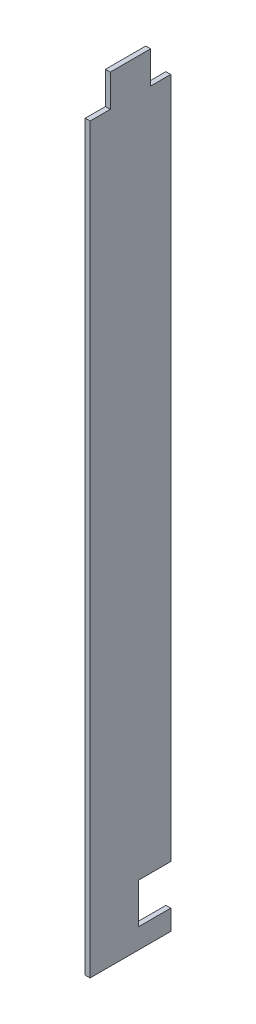
SolidWorks part; units mm, degrees
ref_plane "Plan de face" through (0, 0, 0) normal (0, 0, 1) x (1, 0, 0)
ref_plane "Plan de dessus" through (0, 0, 0) normal (0, 1, 0) x (1, 0, 0)
ref_plane "Plan de droite" through (0, 0, 0) normal (1, 0, 0) x (0, 0, -1)
sketch "Esquisse1" plane through (0, 0, 0) normal (1, 0, 0) x (0, 0, -1)
  line L1 (25, -230) -> (-25, -230)
  line L2 (25, -230) -> (25, 230)
  line L3 (25, 230) -> (-25, 230)
  line L4 (-25, -230) -> (-25, 230)
  line L5 (25, -230) -> (-25, 230) construction
  line L6 (25, 230) -> (-25, -230) construction
  point P0 (0, 0)
  dimension "D1" = 50
  dimension "D2" = 460
extrude "Boss.-Extru.1" add sketch "Esquisse1" along normal blind 3
sketch "Esquisse2" plane through (3, 0, 0) normal (1, 0, 0) x (0, 0, -1)
  line L0 (25, 230) -> (-25, 230) construction
  line L1 (-12.5, 230) -> (12.5, 230)
  line L5 (25, -230) -> (25, 230) construction
  line L6 (25, -217.5) -> (5, -217.5)
  line L7 (25, -217.5) -> (25, -192.5)
  line L8 (25, -192.5) -> (5, -192.5)
  line L9 (5, -217.5) -> (5, -192.5)
  point P1 (0, 0)
  point P14 (0, 0)
  line M3 (25, -230) -> (25, 230)
  dimension "D1" = 12.5
  dimension "D2" = 12.5
  dimension "D3" = 25
  dimension "D4" = 12.5
  dimension "D5" = 20
extrude "Enlèv. mat.-Extru.2" cut sketch "Esquisse2" against normal through all contours L9 L6 L8 M3
sketch "Esquisse5" plane through (3, 0, 0) normal (1, 0, 0) x (0, 0, -1)
  line L0 (25, 230) -> (-25, 230) construction
  line L1 (-12.5, 230) -> (12.5, 230)
  line L2 (-12.5, 230) -> (-12.5, 250)
  line L3 (-12.5, 250) -> (12.5, 250)
  line L4 (12.5, 230) -> (12.5, 250)
  line L5 (25, -192.5) -> (25, 230) construction
  point P9 (0, 0)
  dimension "D1" = 12.5
  dimension "D2" = 12.5
  dimension "D3" = 20
extrude "Boss.-Extru.3" add sketch "Esquisse5" against normal blind 3
